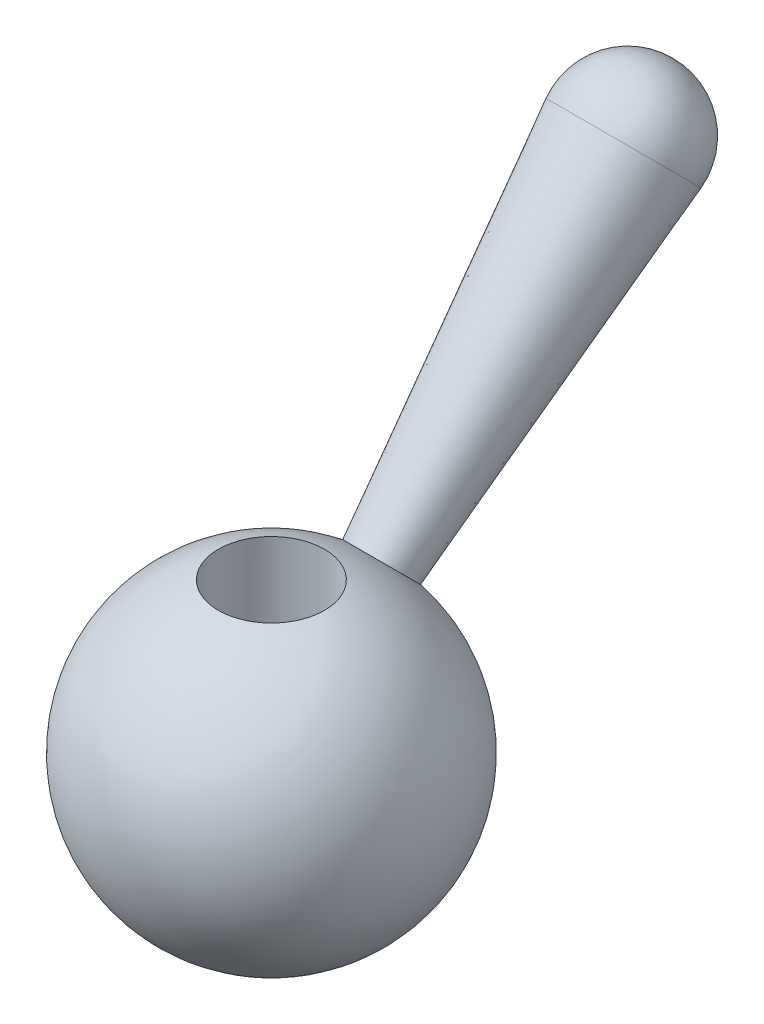
SolidWorks part; units mm, degrees
ref_plane "前视基准面" through (0, 0, 0) normal (0, 0, 1) x (1, 0, 0)
ref_plane "上视基准面" through (0, 0, 0) normal (0, 1, 0) x (1, 0, 0)
ref_plane "右视基准面" through (0, 0, 0) normal (1, 0, 0) x (0, 0, -1)
other "Configuration Table"
sketch "草图1" plane through (0, 0, 0) normal (0, 0, 1) x (1, 0, 0)
  line L0 (0, 30) -> (0, -30)
  arc A0 (0, -30) -> (0, 30) centre (0, 0) ccw
  dimension "D1" = 60
revolve "旋转1" add sketch "草图1" angle 360 about L0
sketch "草图2" plane through (0, 0, 0) normal (0, 1, 0) x (1, 0, 0)
  circle A0 centre (0, 0) radius 10
  dimension "D1" = 20
extrude "切除-拉伸1" cut sketch "草图2" against normal through all both and the other way through all
sketch "草图4" plane through (0, 0, 0) normal (1, 0, 0) x (0, 0, -1)
  line L0 (0, 0) -> (65.9207, 0) construction
  line L1 (0, 0) -> (67.1751, 67.1751) construction
  line L2 (20.7846, 20.7846) -> (25.0273, 16.542)
  line L3 (25.0273, 16.542) -> (74.8453, 57.9464)
  line L4 (20.7846, 20.7846) -> (75.6604, 75.6604)
  arc A0 (74.8453, 57.9464) -> (75.6604, 75.6604) centre (67.1751, 67.1751) ccw
  arc A1 (10, -28.2843) -> (10, 28.2843) centre (0, 0) ccw construction
  dimension "D3" = 24
  dimension "D1" = 45
  dimension "D2" = 95
  dimension "D4" = 6
revolve "旋转10" add sketch "草图4" angle 360 about L4
